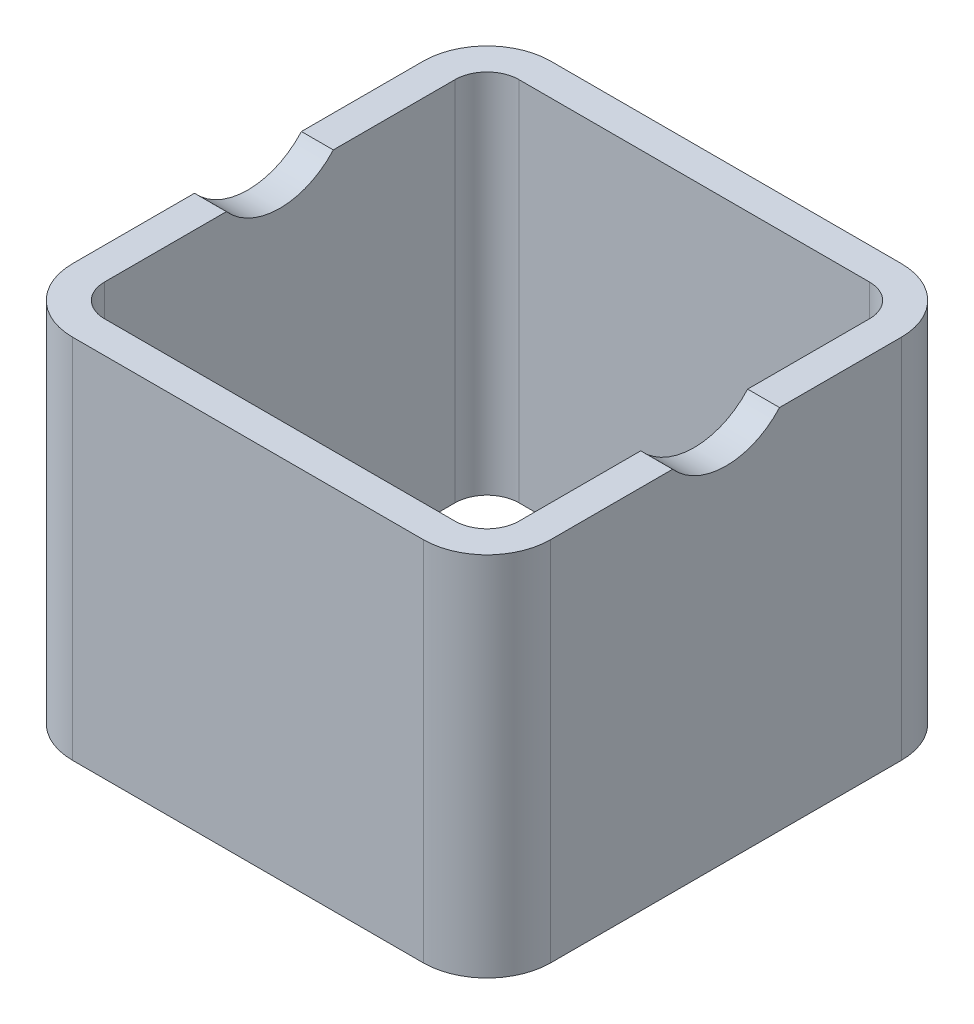
SolidWorks part; units mm, degrees
material "AISI 1010 钢，热轧条材"
ref_plane "前视基准面" through (0, 0, 0) normal (0, 0, 1) x (1, 0, 0)
ref_plane "上视基准面" through (0, 0, 0) normal (0, 1, 0) x (1, 0, 0)
ref_plane "右视基准面" through (0, 0, 0) normal (1, 0, 0) x (0, 0, -1)
sketch "草图1" plane through (0, 0, 0) normal (0, 1, 0) x (1, 0, 0)
  line L0 (-11, -13) -> (11, -13)
  line L1 (-11, -15) -> (11, -15)
  line L2 (-15, -11) -> (-15, 11)
  line L3 (-11, 15) -> (11, 15)
  line L4 (15, -11) -> (15, 11)
  line L5 (13, -11) -> (13, 11)
  line L6 (-11, 13) -> (11, 13)
  line L7 (-13, -11) -> (-13, 11)
  arc A0 (-11, -15) -> (-15, -11) centre (-11, -11) cw
  arc A1 (11, -15) -> (15, -11) centre (11, -11) ccw
  arc A2 (11, 15) -> (15, 11) centre (11, 11) cw
  arc A3 (-15, 11) -> (-11, 15) centre (-11, 11) cw
  arc A4 (11, -13) -> (13, -11) centre (11, -11) ccw
  arc A5 (11, 13) -> (13, 11) centre (11, 11) cw
  arc A6 (-13, 11) -> (-11, 13) centre (-11, 11) cw
  arc A7 (-11, -13) -> (-13, -11) centre (-11, -11) cw
  point P4 (-15, 0)
  point P7 (-15, -15)
  point P10 (15, -15)
  point P13 (15, 15)
  point P16 (-15, 15)
  point P30 (0, 15)
  dimension "D3" = 4
  dimension "D1" = 30
  dimension "D2" = 30
  dimension "D4" = 2
extrude "凸台-拉伸1" add sketch "草图1" along normal mid plane 23
sketch "草图2" plane through (0, 0, 0) normal (1, 0, 0) x (0, 0, -1)
  line L0 (0, 41.5) -> (29.3061, 41.5) construction
  line L1 (-11, -11.5) -> (11, -11.5) construction
  line L2 (-11, 11.5) -> (11, 11.5) construction
  circle A0 centre (0, 14.5) radius 4.5
  point P9 (0, 11.5)
  dimension "D1" = 9
  dimension "D2" = 53
  dimension "D3" = 27
extrude "切除-拉伸1" cut sketch "草图2" against normal through all both and the other way through all
